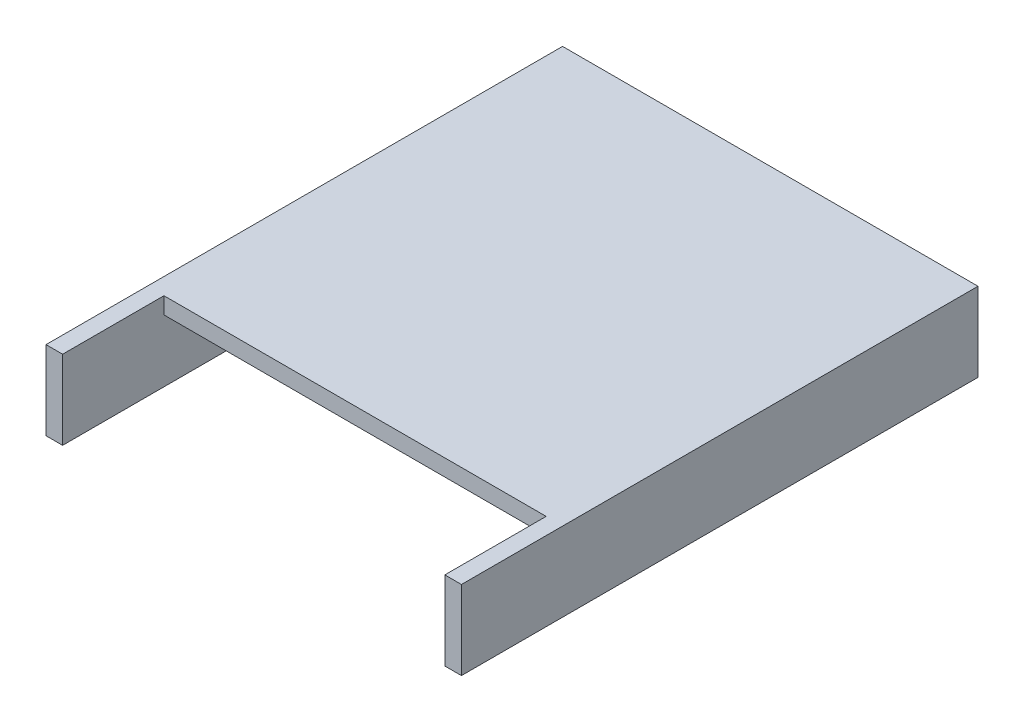
SolidWorks part; units mm, degrees
ref_plane "Front Plane" through (0, 0, 0) normal (0, 0, 1) x (1, 0, 0)
ref_plane "Top Plane" through (0, 0, 0) normal (0, 1, 0) x (1, 0, 0)
ref_plane "Right Plane" through (0, 0, 0) normal (1, 0, 0) x (0, 0, -1)
sketch "Sketch1" plane through (0, 0, 0) normal (0, 0, 1) x (1, 0, 0)
  line L0 (52.6486, 19.6667) -> (56.6486, 19.6667)
  line L1 (-43.3514, 19.6667) -> (-39.3514, 19.6667)
  line L2 (-43.3514, 19.6667) -> (-43.3514, 38.6667)
  line L3 (-43.3514, 38.6667) -> (56.6486, 38.6667)
  line L4 (56.6486, 19.6667) -> (56.6486, 38.6667)
  line L6 (-39.3514, 19.6667) -> (-39.3514, 34.6667)
  line L7 (-39.3514, 34.6667) -> (52.6486, 34.6667)
  line L8 (52.6486, 19.6667) -> (52.6486, 34.6667)
  dimension "D1" = 100
  dimension "D2" = 92
  dimension "D3" = 4
  dimension "D4" = 4
  dimension "D5" = 15
extrude "Boss-Extrude1" add sketch "Sketch1" along normal blind 99.95 contours L7 L8 L0 L4 L3 L2 L1 L6
sketch "Sketch2" plane through (0, 0, 99.95) normal (0, 0, 1) x (1, 0, 0)
  line L1 (-43.3514, 38.6667) -> (-39.3514, 38.6667)
  line L2 (-43.3514, 38.6667) -> (-43.3514, 19.6667)
  line L3 (-43.3514, 19.6667) -> (-39.3514, 19.6667)
  line L4 (-39.3514, 38.6667) -> (-39.3514, 19.6667)
  line L5 (56.6486, 38.6667) -> (52.6486, 38.6667)
  line L6 (56.6486, 38.6667) -> (56.6486, 19.6667)
  line L7 (56.6486, 19.6667) -> (52.6486, 19.6667)
  line L8 (52.6486, 38.6667) -> (52.6486, 19.6667)
extrude "Boss-Extrude2" add sketch "Sketch2" along normal blind 24.39
